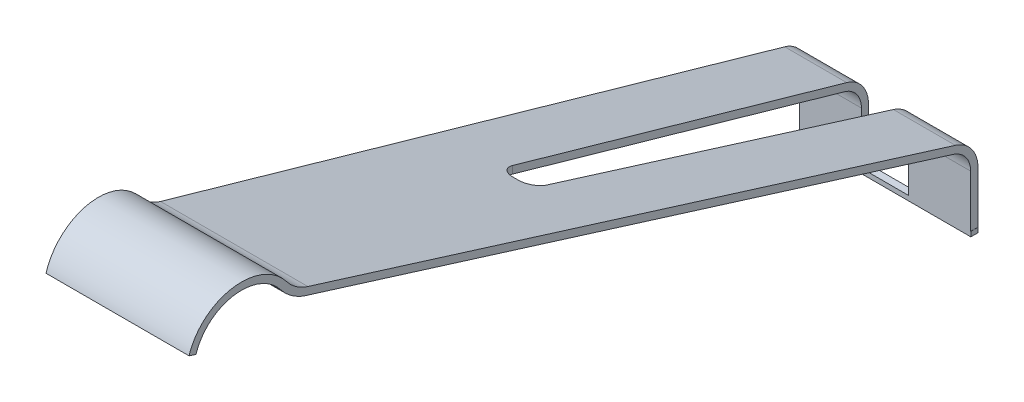
SolidWorks part; units mm, degrees
ref_plane "Спереди" through (0, 0, 0) normal (0, 0, 1) x (1, 0, 0)
ref_plane "Сверху" through (0, 0, 0) normal (0, 1, 0) x (1, 0, 0)
ref_plane "Справа" through (0, 0, 0) normal (1, 0, 0) x (0, 0, -1)
ref_plane "MidPlane" through (2.85, 0, 0) normal (1, 0, 0) x (0, 0, -1)
sketch "Эскиз1" plane through (2.85, 0, 0) normal (1, 0, 0) x (0, 0, -1)
  line L0 (5.55, 4.85) -> (5.55, 6.0428)
  line L1 (5.193, 6.5219) -> (-8.145, 10.5036)
  line L2 (-11.8952, 11.25) -> (-5.2752, 11.25) construction
  line L3 (5.3, 4.85) -> (5.8, 4.85) construction
  line L4 (5.8, 4.85) -> (5.3, 4.85) construction
  line L5 (-9.45, 12.3334) -> (-9.45, 9.342) construction
  arc A0 (-8.6545, 10.8559) -> (-10.4056, 10.5446) centre (-9.45, 10.25) ccw
  arc A1 (5.55, 6.0428) -> (5.193, 6.5219) centre (5.05, 6.0428) ccw
  arc A2 (-8.145, 10.5036) -> (-8.6545, 10.8559) centre (-7.8589, 11.4618) cw
  point P13 (5.55, 4.85)
  dimension "D1" = 0.5
  dimension "D4" = 1
  dimension "D5" = 1
  dimension "D2" = 15
  dimension "D3" = 12.8
extrude "Hook_Lever" add sketch "Эскиз1" along normal blind 1.8 and the other way blind 1.8 thin
sketch "Эскиз2" plane through (0, 4.95, 0) normal (0, 1, 0) x (1, 0, 0)
  line L0 (1.35, -10.549) -> (4.35, -10.549) construction
  line L1 (2.85, -3.3) -> (2.85, 3.3) construction
  line L2 (4.65, 5.8) -> (1.05, 5.8) construction
  line L4 (1.05, 5.8) -> (1.35, -10.549)
  line L6 (1.05, 5.8) -> (1.05, -10.549)
  line L7 (1.05, -10.549) -> (1.35, -10.549)
  line L8 (2.85, 9.5236) -> (2.85, -8.0095) construction
  line L10 (4.65, 5.8) -> (4.65, -10.549)
  line L11 (4.65, 5.8) -> (4.35, -10.549)
  line L12 (4.65, -10.549) -> (4.35, -10.549)
  line L13 (2.35, 5.8) -> (3.35, 5.8)
  line L15 (2.7944, -2.2) -> (2.9056, -2.2)
  line L16 (2.4945, -1.9056) -> (2.35, 5.8)
  line L17 (3.2055, -1.9056) -> (3.35, 5.8)
  line L18 (1.05, -10.549) -> (4.65, -10.549) construction
  arc A0 (2.9056, -2.2) -> (3.2055, -1.9056) centre (2.9056, -1.9) ccw
  arc A1 (2.7944, -2.2) -> (2.4945, -1.9056) centre (2.7944, -1.9) cw
  point P5 (2.85, -10.549)
  point P22 (2.85, 5.8)
  point P25 (2.85, -2.2)
  point P27 (3.2, -2.2)
  point P30 (2.5, -2.2)
  dimension "D5" = 0.3
  dimension "D1" = 3
  dimension "D2" = 8
  dimension "D3" = 1
  dimension "D4" = 0.7
extrude "Cut" cut sketch "Эскиз2" along normal through all
